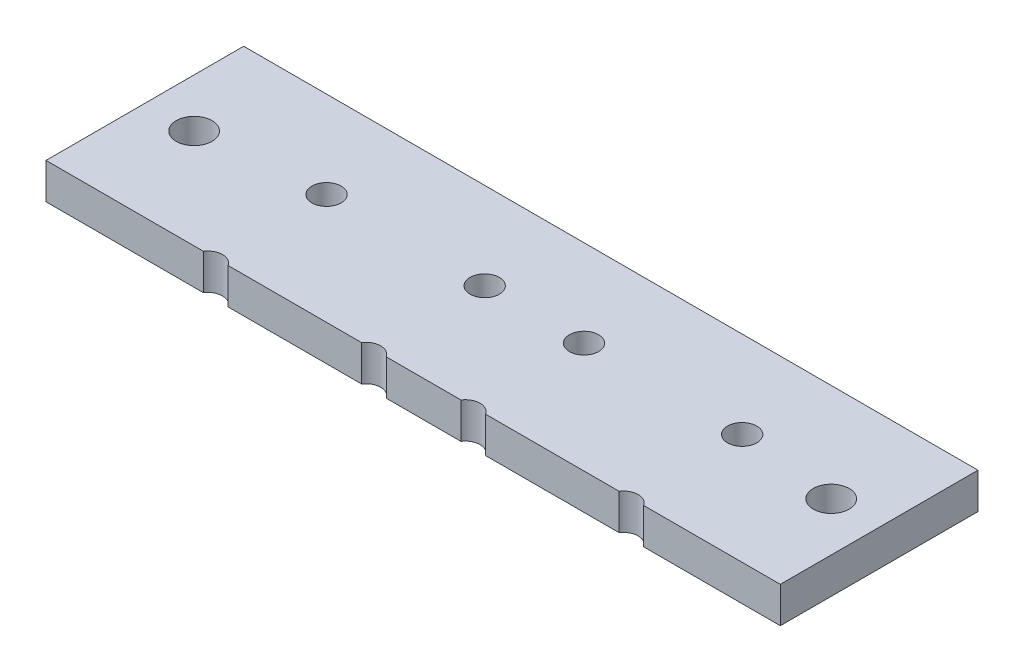
SolidWorks part; units mm, degrees
material "Alumina"
ref_plane "Front Plane" through (0, 0, 0) normal (0, 0, 1) x (1, 0, 0)
ref_plane "Top Plane" through (0, 0, 0) normal (0, 1, 0) x (1, 0, 0)
ref_plane "Right Plane" through (0, 0, 0) normal (1, 0, 0) x (0, 0, -1)
sketch "Sketch1" plane through (0, 0, 0) normal (0, 1, 0) x (1, 0, 0)
  line L1 (0, 0) -> (130, 0)
  line L2 (0, 0) -> (0, -35)
  line L3 (0, -35) -> (130, -35)
  line L4 (130, 0) -> (130, -35)
  dimension "D1" = 130
  dimension "D2" = 35
extrude "Boss-Extrude1" add sketch "Sketch1" along normal blind 6.35
sketch "Sketch5" plane through (0, 6.35, 0) normal (0, 1, 0) x (1, 0, 0)
  line L1 (0, 0) -> (0, -35) construction
  line L2 (130, -35) -> (130, 0) construction
  circle A0 centre (8.605, -17.3826) radius 3.18
  circle A2 centre (121.395, -17.3826) radius 3.18
  dimension "D1" = 8.605
  dimension "D2" = 8.605
extrude "Cut-Extrude2" cut sketch "Sketch5" against normal through all
sketch "Sketch8" plane through (0, 0, 0) normal (0, -1, 0) x (1, 0, 0)
  circle A16 centre (30.0602, 15.3965) radius 2.5866 construction
  circle A17 centre (30.0602, 36.3965) radius 2.5866 construction
  circle A18 centre (58.0602, 36.3965) radius 2.5866 construction
  circle A19 centre (58.0602, 15.3965) radius 2.5866 construction
  circle A20 centre (75.6421, 15.3965) radius 2.5866 construction
  circle A21 centre (75.6421, 36.3965) radius 2.5866 construction
  circle A22 centre (103.6421, 15.3965) radius 2.5866 construction
  circle A23 centre (103.6421, 36.3965) radius 2.5866 construction
  circle A24 centre (30.0602, 15.3965) radius 2.5866
  circle A25 centre (30.0602, 36.3965) radius 2.5866
  circle A26 centre (58.0602, 36.3965) radius 2.5866
  circle A27 centre (58.0602, 15.3965) radius 2.5866
  circle A28 centre (75.6421, 15.3965) radius 2.5866
  circle A29 centre (75.6421, 36.3965) radius 2.5866
  circle A30 centre (103.6421, 15.3965) radius 2.5866
  circle A31 centre (103.6421, 36.3965) radius 2.5866
extrude "Cut-Extrude4" cut sketch "Sketch8" against normal through all
